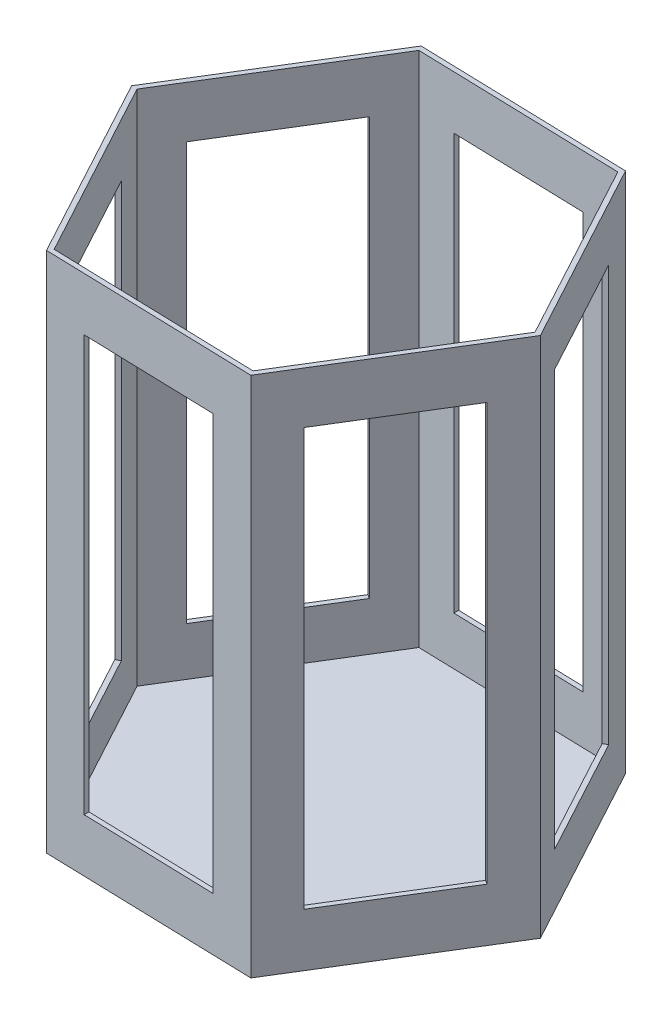
SolidWorks part; units mm, degrees
ref_plane "Alzado" through (0, 0, 0) normal (0, 0, 1) x (1, 0, 0)
ref_plane "Planta" through (0, 0, 0) normal (0, 1, 0) x (1, 0, 0)
ref_plane "Vista lateral" through (0, 0, 0) normal (1, 0, 0) x (0, 0, -1)
sketch "Croquis1" plane through (0, 0, 0) normal (0, 1, 0) x (1, 0, 0)
  line L1 (-87, 2.4696) -> (-45.6387, -74.1094)
  line L2 (-45.6387, -74.1094) -> (41.3613, -76.579)
  line L3 (41.3613, -76.579) -> (87, -2.4696)
  line L4 (87, -2.4696) -> (45.6387, 74.1094)
  line L5 (45.6387, 74.1094) -> (-41.3613, 76.579)
  line L6 (-41.3613, 76.579) -> (-87, 2.4696)
  circle A0 centre (0, 0) radius 75.3746 construction
  dimension "D1" = 150.7491
  dimension "D2" = 87
extrude "Saliente-Extruir1" add sketch "Croquis1" against normal blind 215.9
shell "Vaciado2" thickness 2
sketch "Croquis2" plane through (-2.1387, 0, 75.3442) normal (-0.0284, 0, 0.9996) x (0.9996, 0, 0.0284)
  line L0 (-43.5175, 0) -> (43.5175, 0) construction
  line L1 (-27.5, -22) -> (27.5, -22)
  line L2 (-27.5, -22) -> (-27.5, -193.9)
  line L3 (-27.5, -193.9) -> (27.5, -193.9)
  line L4 (27.5, -22) -> (27.5, -193.9)
  line L5 (-43.5175, -215.9) -> (43.5175, -215.9) construction
  line L6 (0, 0) -> (0, -215.9) construction
  point P10 (0, -22)
  dimension "D1" = 22
  dimension "D2" = 55
  dimension "D3" = 22
extrude "Cortar-Extruir1" cut sketch "Croquis2" against normal blind 215.9
sketch "Croquis3" plane through (64.1806, 0, 39.5243) normal (0.8515, 0, 0.5244) x (0.5244, 0, -0.8515)
  line L0 (0, 0) -> (0, -215.9) construction
  line L1 (-43.5175, 0) -> (43.5175, 0) construction
  line L2 (-43.5175, -215.9) -> (43.5175, -215.9) construction
  line L4 (-27.5, -21.3389) -> (27.5, -21.3389)
  line L5 (-27.5, -21.3389) -> (-27.5, -193.9)
  line L6 (-27.5, -193.9) -> (27.5, -193.9)
  line L7 (27.5, -21.3389) -> (27.5, -193.9)
  point P10 (0, -21.3389)
  dimension "D1" = 55
  dimension "D2" = 21.3389
  dimension "D3" = 22
extrude "Cortar-Extruir2" cut sketch "Croquis3" against normal blind 215.9
sketch "Croquis4" plane through (66.3194, 0, -35.8199) normal (0.8799, 0, -0.4752) x (-0.4752, 0, -0.8799)
  line L0 (0, 0) -> (0, -215.9) construction
  line L1 (-28.8242, -22) -> (26.3298, -22)
  line L2 (-28.8242, -22) -> (-28.8242, -193.9)
  line L3 (-28.8242, -193.9) -> (26.3298, -193.9)
  line L4 (26.3298, -22) -> (26.3298, -193.9)
  line L5 (-43.5175, -215.9) -> (43.5175, -215.9) construction
  line L6 (-43.5175, 0) -> (43.5175, 0) construction
  dimension "D1" = 22
  dimension "D2" = 55.1539
  dimension "D3" = 22
extrude "Cortar-Extruir3" cut sketch "Croquis4" against normal blind 215.9
